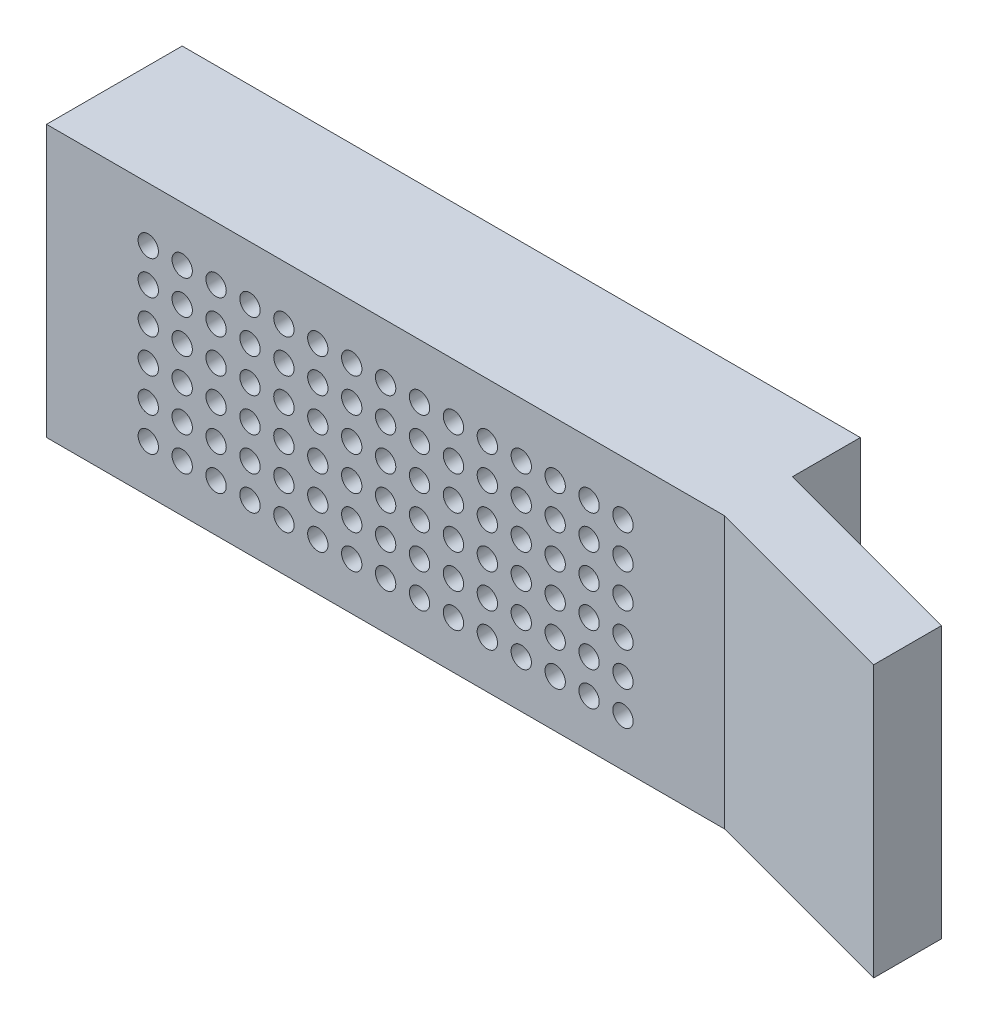
SolidWorks part; units mm, degrees
ref_plane "前视基准面" through (0, 0, 0) normal (0, 0, 1) x (1, 0, 0)
ref_plane "上视基准面" through (0, 0, 0) normal (0, 1, 0) x (1, 0, 0)
ref_plane "右视基准面" through (0, 0, 0) normal (1, 0, 0) x (0, 0, -1)
other "Configuration Table"
sketch "草图1" plane through (0, 0, 0) normal (0, 0, 1) x (1, 0, 0)
  line L1 (-50, 20) -> (50, 20)
  line L2 (-50, 20) -> (-50, -20)
  line L3 (-50, -20) -> (50, -20)
  line L4 (50, 20) -> (50, -20)
  dimension "D1" = 100
  dimension "D2" = 40
  dimension "D3" = 20
  dimension "D4" = 50
extrude "凸台-拉伸1" add sketch "草图1" along normal blind 20
shell "抽壳1" thickness 3
sketch "草图3" plane through (0, 20, 0) normal (0, 1, 0) x (1, 0, 0)
  line L0 (50, -20) -> (80, -28.0385)
  line L1 (80, -28.0385) -> (80, -18.0385)
  line L2 (80, -18.0385) -> (50, -10)
  line L3 (50, -10) -> (50, -20)
  line L4 (50, -20) -> (50, 0) construction
  dimension "D1" = 10
  dimension "D2" = 75
  dimension "D3" = 30
extrude "凸台-拉伸2" add sketch "草图3" against normal blind 40
sketch "草图4" plane through (0, 0, 0) normal (0, 0, -1) x (-1, 0, 0)
  line L0 (-50, 20) -> (50, 20) construction
  line L1 (-50, -20) -> (-50, 20) construction
  line L2 (0, 0) -> (0, 50000) construction
  line L3 (0, 0) -> (50000, 0) construction
  circle A0 centre (-45, 15) radius 5
  circle A1 centre (45, 15) radius 5
  circle A2 centre (45, -15) radius 5
  circle A3 centre (-45, -15) radius 5
  dimension "D1" = 10
extrude "凸台-拉伸3" add sketch "草图4" against normal blind 20
sketch "草图5" plane through (0, 0, 0) normal (0, 0, -1) x (-1, 0, 0)
  circle A0 centre (-45, 15) radius 1.5
  circle A1 centre (45, 15) radius 1.5
  circle A2 centre (45, -15) radius 1.5
  circle A3 centre (-45, -15) radius 1.5
  dimension "D1" = 3
extrude "切除-拉伸1" cut sketch "草图5" against normal blind 16
sketch "草图6" plane through (0, 0, 17) normal (0, 0, -1) x (-1, 0, 0)
  line L0 (-40.4174, 17) -> (40.4174, 17) construction
  line L1 (50, 20) -> (50, -20) construction
  circle A0 centre (35, 12) radius 1.5
  circle A1 centre (30, 12) radius 1.5
  circle A2 centre (25, 12) radius 1.5
  circle A3 centre (20, 12) radius 1.5
  circle A4 centre (15, 12) radius 1.5
  circle A5 centre (10, 12) radius 1.5
  circle A6 centre (5, 12) radius 1.5
  circle A7 centre (0, 12) radius 1.5
  circle A8 centre (-5, 12) radius 1.5
  circle A9 centre (-10, 12) radius 1.5
  circle A10 centre (-15, 12) radius 1.5
  circle A11 centre (-20, 12) radius 1.5
  circle A12 centre (-25, 12) radius 1.5
  circle A13 centre (-30, 12) radius 1.5
  circle A14 centre (-35, 12) radius 1.5
  circle A15 centre (30, 7) radius 1.5
  circle A16 centre (25, 7) radius 1.5
  circle A17 centre (20, 7) radius 1.5
  circle A18 centre (15, 7) radius 1.5
  circle A19 centre (10, 7) radius 1.5
  circle A20 centre (5, 7) radius 1.5
  circle A21 centre (0, 7) radius 1.5
  circle A22 centre (-5, 7) radius 1.5
  circle A23 centre (-10, 7) radius 1.5
  circle A24 centre (-15, 7) radius 1.5
  circle A25 centre (-20, 7) radius 1.5
  circle A26 centre (-25, 7) radius 1.5
  circle A27 centre (-30, 7) radius 1.5
  circle A28 centre (-35, 7) radius 1.5
  circle A29 centre (30, 2) radius 1.5
  circle A30 centre (25, 2) radius 1.5
  circle A31 centre (20, 2) radius 1.5
  circle A32 centre (15, 2) radius 1.5
  circle A33 centre (10, 2) radius 1.5
  circle A34 centre (5, 2) radius 1.5
  circle A35 centre (0, 2) radius 1.5
  circle A36 centre (-5, 2) radius 1.5
  circle A37 centre (-10, 2) radius 1.5
  circle A38 centre (-15, 2) radius 1.5
  circle A39 centre (-20, 2) radius 1.5
  circle A40 centre (-25, 2) radius 1.5
  circle A41 centre (-30, 2) radius 1.5
  circle A42 centre (-35, 2) radius 1.5
  circle A43 centre (30, -3) radius 1.5
  circle A44 centre (25, -3) radius 1.5
  circle A45 centre (20, -3) radius 1.5
  circle A46 centre (15, -3) radius 1.5
  circle A47 centre (10, -3) radius 1.5
  circle A48 centre (5, -3) radius 1.5
  circle A49 centre (0, -3) radius 1.5
  circle A50 centre (-5, -3) radius 1.5
  circle A51 centre (-10, -3) radius 1.5
  circle A52 centre (-15, -3) radius 1.5
  circle A53 centre (-20, -3) radius 1.5
  circle A54 centre (-25, -3) radius 1.5
  circle A55 centre (-30, -3) radius 1.5
  circle A56 centre (-35, -3) radius 1.5
  circle A57 centre (30, -8) radius 1.5
  circle A58 centre (25, -8) radius 1.5
  circle A59 centre (20, -8) radius 1.5
  circle A60 centre (15, -8) radius 1.5
  circle A61 centre (10, -8) radius 1.5
  circle A62 centre (5, -8) radius 1.5
  circle A63 centre (0, -8) radius 1.5
  circle A64 centre (-5, -8) radius 1.5
  circle A65 centre (-10, -8) radius 1.5
  circle A66 centre (-15, -8) radius 1.5
  circle A67 centre (-20, -8) radius 1.5
  circle A68 centre (-25, -8) radius 1.5
  circle A69 centre (-30, -8) radius 1.5
  circle A70 centre (-35, -8) radius 1.5
  circle A71 centre (30, -13) radius 1.5
  circle A72 centre (25, -13) radius 1.5
  circle A73 centre (20, -13) radius 1.5
  circle A74 centre (15, -13) radius 1.5
  circle A75 centre (10, -13) radius 1.5
  circle A76 centre (5, -13) radius 1.5
  circle A77 centre (0, -13) radius 1.5
  circle A78 centre (-5, -13) radius 1.5
  circle A79 centre (-10, -13) radius 1.5
  circle A80 centre (-15, -13) radius 1.5
  circle A81 centre (-20, -13) radius 1.5
  circle A82 centre (-25, -13) radius 1.5
  circle A83 centre (-30, -13) radius 1.5
  circle A84 centre (-35, -13) radius 1.5
  circle A85 centre (35, 7) radius 1.5
  circle A86 centre (35, 2) radius 1.5
  circle A87 centre (35, -3) radius 1.5
  circle A88 centre (35, -8) radius 1.5
  circle A89 centre (35, -13) radius 1.5
  dimension "D1" = 3
  dimension "D2" = 5
  dimension "D3" = 15
  dimension "D4" = 15
  dimension "D5" = 6
extrude "切除-拉伸2" cut sketch "草图6" against normal blind 10
